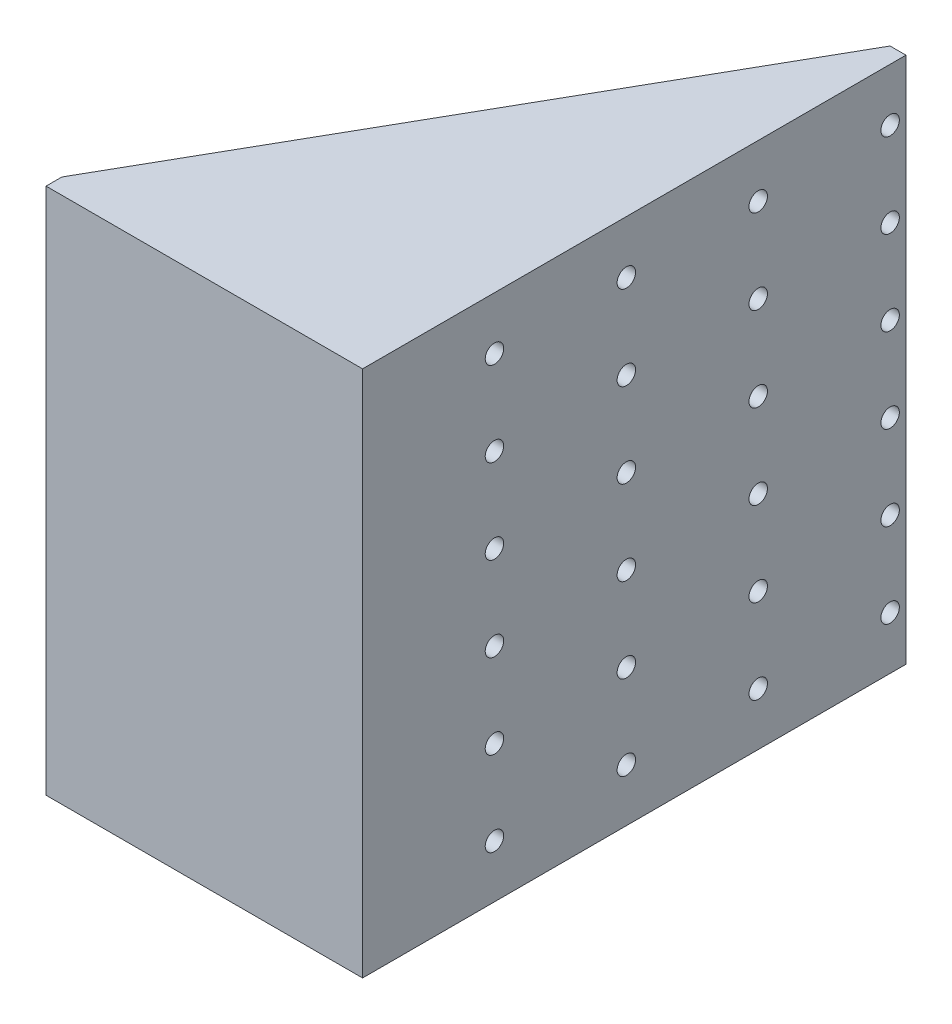
SolidWorks part; units mm, degrees
ref_plane "前视基准面" through (0, 0, 0) normal (0, 0, 1) x (1, 0, 0)
ref_plane "上视基准面" through (0, 0, 0) normal (0, 1, 0) x (1, 0, 0)
ref_plane "右视基准面" through (0, 0, 0) normal (1, 0, 0) x (0, 0, -1)
other "Configuration Table"
sketch "Sketch1" plane through (0, 0, 0) normal (0, 1, 0) x (1, 0, 0)
  line L0 (0, 0) -> (-60, 0)
  line L1 (-60, 0) -> (-60, 3)
  line L2 (-60, 3) -> (-3, 3)
  line L3 (-3, 3) -> (-3, 103)
  line L4 (-3, 103) -> (0, 103)
  line L5 (0, 103) -> (0, 0)
  dimension "D1" = 3
  dimension "D2" = 3
  dimension "D3" = 60
  dimension "D4" = 100
extrude "Boss-Extrude1" add sketch "Sketch1" along normal blind 100
sketch "Sketch2" plane through (0, 100, 0) normal (0, 1, 0) x (1, 0, 0)
  line L0 (-60, 3) -> (-3, 103)
  line L1 (-3, 103) -> (-3, 3)
  line L2 (-3, 3) -> (-60, 3)
extrude "Boss-Extrude2" add sketch "Sketch2" against normal blind 4
pattern_linear "LPattern1" count 7 spacing 16 along (0, -1, 0) of "Boss-Extrude2"
sketch "Sketch3" plane through (0, 0, 0) normal (1, 0, 0) x (0, 0, -1)
  line L0 (0, 0) -> (25, 0) construction
  line L1 (0, 0) -> (103, 0) construction
  line L2 (25, 0) -> (25, 10) construction
  circle A0 centre (25, 10) radius 1.75
  circle A1 centre (50, 10) radius 1.75
  circle A2 centre (75, 10) radius 1.75
  circle A3 centre (100, 10) radius 1.75
  circle A4 centre (50, 26) radius 1.75
  circle A5 centre (75, 26) radius 1.75
  circle A6 centre (100, 26) radius 1.75
  circle A7 centre (50, 42) radius 1.75
  circle A8 centre (75, 42) radius 1.75
  circle A9 centre (100, 42) radius 1.75
  circle A10 centre (50, 58) radius 1.75
  circle A11 centre (75, 58) radius 1.75
  circle A12 centre (100, 58) radius 1.75
  circle A13 centre (50, 74) radius 1.75
  circle A14 centre (75, 74) radius 1.75
  circle A15 centre (100, 74) radius 1.75
  circle A16 centre (50, 90) radius 1.75
  circle A17 centre (75, 90) radius 1.75
  circle A18 centre (100, 90) radius 1.75
  circle A19 centre (25, 26) radius 1.75
  circle A20 centre (25, 42) radius 1.75
  circle A21 centre (25, 58) radius 1.75
  circle A22 centre (25, 74) radius 1.75
  circle A23 centre (25, 90) radius 1.75
  dimension "D3" = 3.5
  dimension "D1" = 25
  dimension "D2" = 10
  dimension "D4" = 4
  dimension "D5" = 6
extrude "Cut-Extrude1" cut sketch "Sketch3" against normal blind 10
